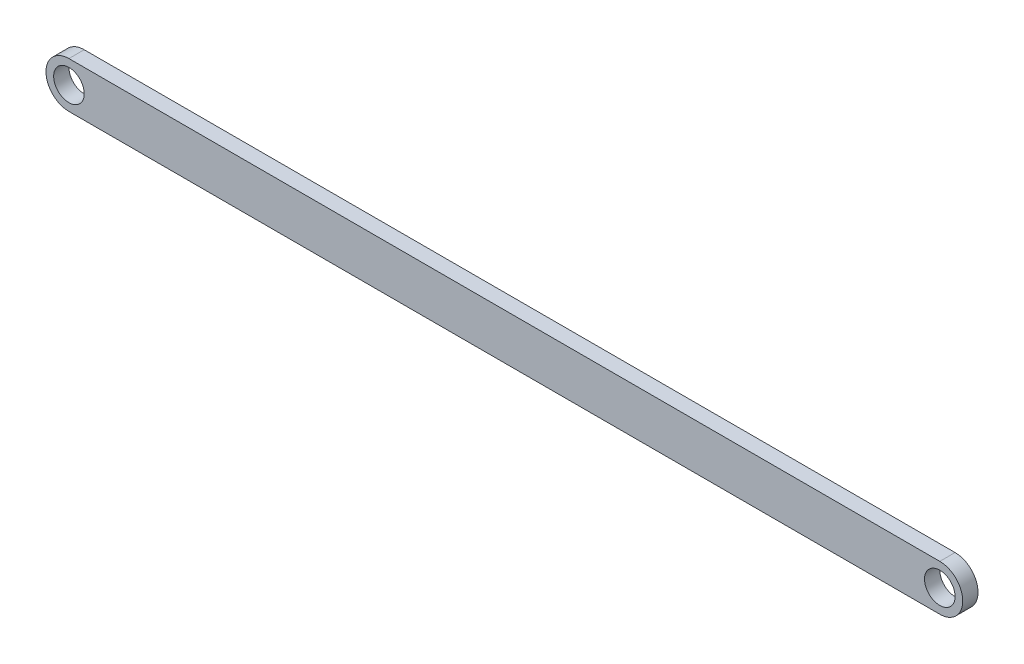
SolidWorks part; units mm, degrees
ref_plane "Спереди" through (0, 0, 0) normal (0, 0, 1) x (1, 0, 0)
ref_plane "Сверху" through (0, 0, 0) normal (0, 1, 0) x (1, 0, 0)
ref_plane "Справа" through (0, 0, 0) normal (1, 0, 0) x (0, 0, -1)
other "Configuration Table"
sketch "Эскиз1" plane through (0, 0, 0) normal (0, 0, 1) x (1, 0, 0)
  line L0 (0, 0) -> (570, 0) construction
  line L1 (0, 15) -> (570, 15)
  line L2 (0, -15) -> (570, -15)
  arc A0 (0, 15) -> (0, -15) centre (0, 0) ccw
  arc A1 (570, -15) -> (570, 15) centre (570, 0) ccw
  circle A2 centre (0, 0) radius 10
  circle A3 centre (570, 0) radius 10
  point P3 (285, 0)
  dimension "D1" = 570
  dimension "D2" = 30
extrude "Бобышка-Вытянуть1" add sketch "Эскиз1" along normal blind 10
